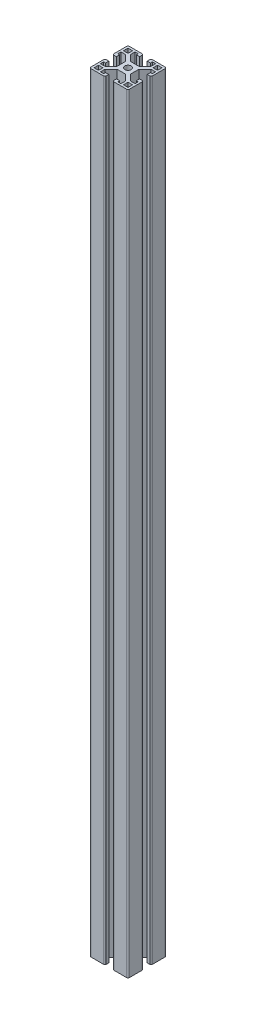
SolidWorks part; units mm, degrees
material "1060 Alloy"
ref_plane "Front Plane" through (0, 0, 0) normal (0, 0, 1) x (1, 0, 0)
ref_plane "Top Plane" through (0, 0, 0) normal (0, 1, 0) x (1, 0, 0)
ref_plane "Right Plane" through (0, 0, 0) normal (1, 0, 0) x (0, 0, -1)
sketch "Sketch1" plane through (0, 0, 0) normal (0, 1, 0) x (1, 0, 0)
  line L0 (-15, 7.5) -> (-15, -4.5)
  line L1 (-15, 7.5) -> (15, 7.5) construction
  line L2 (-15, 7.5) -> (-15, -7.5) construction
  line L3 (-15, -7.5) -> (15, -7.5) construction
  line L4 (15, 7.5) -> (15, -7.5) construction
  line L5 (0, -7.5) -> (0, 7.5) construction
  line L6 (-15, 0) -> (15, 0) construction
  line L7 (-15, 7.5) -> (-3, 7.5)
  line L8 (-15, -4.5) -> (-12, -4.5)
  line L9 (-12, -4.5) -> (-12, -2)
  line L10 (-12, -2) -> (-13.5, -2)
  line L11 (-13.5, -2) -> (-13.5, 0.5)
  line L12 (-13.5, 0.5) -> (-10, 0.5)
  line L13 (-5.25, -2.25) -> (5.25, -2.25) construction
  line L14 (-5.25, -2.25) -> (-5.25, -12.75) construction
  line L15 (-5.25, -12.75) -> (5.25, -12.75) construction
  line L16 (5.25, -2.25) -> (5.25, -12.75) construction
  line L17 (0, -12.75) -> (0, -2.25) construction
  line L18 (-5.25, -7.5) -> (5.25, -7.5) construction
  line L19 (-2.5857, -4.9143) -> (-15, 7.5) construction
  line L20 (-10, 0.5) -> (-5.25, -4.25)
  line L21 (-8, 2.5) -> (-3.25, -2.25)
  line L22 (-3, 7.5) -> (-3, 4.5)
  line L23 (-3, 4.5) -> (-5.5, 4.5)
  line L24 (-5.5, 4.5) -> (-5.5, 6)
  line L25 (-5.5, 6) -> (-8, 6)
  line L26 (-8, 6) -> (-8, 2.5)
  line L27 (5.5, 4.5) -> (5.5, 6)
  line L28 (-13.25, 5.75) -> (-9.75, 5.75)
  line L29 (-13.25, 5.75) -> (-13.25, 2.25)
  line L30 (-13.25, 2.25) -> (-9.75, 2.25)
  line L31 (-9.75, 5.75) -> (-9.75, 2.25)
  line L32 (-11.5, 2.25) -> (-11.5, 5.75) construction
  line L33 (-13.25, 4) -> (-9.75, 4) construction
  line L34 (13.25, 2.25) -> (9.75, 2.25)
  line L35 (13.25, 5.75) -> (13.25, 2.25)
  line L36 (13.25, 5.75) -> (9.75, 5.75)
  line L37 (9.75, 5.75) -> (9.75, 2.25)
  line L38 (3, 4.5) -> (5.5, 4.5)
  line L39 (3, 7.5) -> (3, 4.5)
  line L40 (5.5, 6) -> (8, 6)
  line L41 (8, 6) -> (8, 2.5)
  line L42 (15, 7.5) -> (3, 7.5)
  line L43 (13.5, 0.5) -> (10, 0.5)
  line L44 (13.5, -2) -> (13.5, 0.5)
  line L45 (12, -2) -> (13.5, -2)
  line L46 (15, 7.5) -> (15, -4.5)
  line L47 (15, -4.5) -> (12, -4.5)
  line L48 (12, -4.5) -> (12, -2)
  line L49 (8, 2.5) -> (3.25, -2.25)
  line L50 (10, 0.5) -> (5.25, -4.25)
  line L51 (-5.25, -4.25) -> (-5.25, -10.75)
  line L52 (-3.25, -2.25) -> (3.25, -2.25)
  line L53 (5.25, -4.25) -> (5.25, -10.75)
  line L54 (15, -22.5) -> (15, -10.5)
  line L55 (15, -10.5) -> (12, -10.5)
  line L56 (12, -10.5) -> (12, -13)
  line L57 (12, -13) -> (13.5, -13)
  line L58 (13.5, -13) -> (13.5, -15.5)
  line L59 (13.5, -15.5) -> (10, -15.5)
  line L60 (13.25, -17.25) -> (9.75, -17.25)
  line L61 (13.25, -20.75) -> (13.25, -17.25)
  line L62 (13.25, -20.75) -> (9.75, -20.75)
  line L63 (9.75, -20.75) -> (9.75, -17.25)
  line L64 (8, -21) -> (8, -17.5)
  line L65 (5.5, -21) -> (8, -21)
  line L66 (5.5, -19.5) -> (5.5, -21)
  line L67 (15, -22.5) -> (3, -22.5)
  line L68 (3, -22.5) -> (3, -19.5)
  line L69 (3, -19.5) -> (5.5, -19.5)
  line L70 (10, -15.5) -> (5.25, -10.75)
  line L71 (8, -17.5) -> (3.25, -12.75)
  line L72 (-3, -22.5) -> (-3, -19.5)
  line L73 (-3, -19.5) -> (-5.5, -19.5)
  line L74 (-5.5, -19.5) -> (-5.5, -21)
  line L75 (-5.5, -21) -> (-8, -21)
  line L76 (-8, -21) -> (-8, -17.5)
  line L77 (-15, -22.5) -> (-3, -22.5)
  line L78 (-9.75, -20.75) -> (-9.75, -17.25)
  line L79 (-13.25, -20.75) -> (-9.75, -20.75)
  line L80 (-13.25, -20.75) -> (-13.25, -17.25)
  line L81 (-13.25, -17.25) -> (-9.75, -17.25)
  line L82 (-13.5, -15.5) -> (-10, -15.5)
  line L83 (-13.5, -13) -> (-13.5, -15.5)
  line L84 (-12, -13) -> (-13.5, -13)
  line L85 (-15, -22.5) -> (-15, -10.5)
  line L86 (-15, -10.5) -> (-12, -10.5)
  line L87 (-12, -10.5) -> (-12, -13)
  line L88 (-3.25, -12.75) -> (3.25, -12.75)
  line L89 (-8, -17.5) -> (-3.25, -12.75)
  line L90 (-10, -15.5) -> (-5.25, -10.75)
  circle A0 centre (0, -7.5) radius 2.5
  point P0 (0, 0)
  point P18 (-11.5, 4)
  dimension "D7" = 1.5
  dimension "D19" = 5
  dimension "D1" = 30
  dimension "D2" = 15
  dimension "D3" = 12
  dimension "D4" = 12
  dimension "D5" = 3
  dimension "D6" = 2.5
  dimension "D8" = 2.5
  dimension "D9" = 10.5
  dimension "D10" = 3.5
  dimension "D11" = 45
  dimension "D12" = 3
  dimension "D13" = 2.5
  dimension "D14" = 1.5
  dimension "D15" = 2.5
  dimension "D16" = 3.5
  dimension "D17" = 3.5
  dimension "D18" = 3.5
extrude "Boss-Extrude1" add sketch "Sketch1" against normal blind 600
fillet "Fillet1" radius 1 12 edges at (-15, -300, 4.5) (-15, -300, -7.5) (-3, -300, -7.5) (3, -300, -7.5) (15, -300, 10.5) (15, -300, -7.5) (15, -300, 4.5) (15, -300, 22.5) (3, -300, 22.5) (-15, -300, 10.5) (-3, -300, 22.5) (-15, -300, 22.5)
